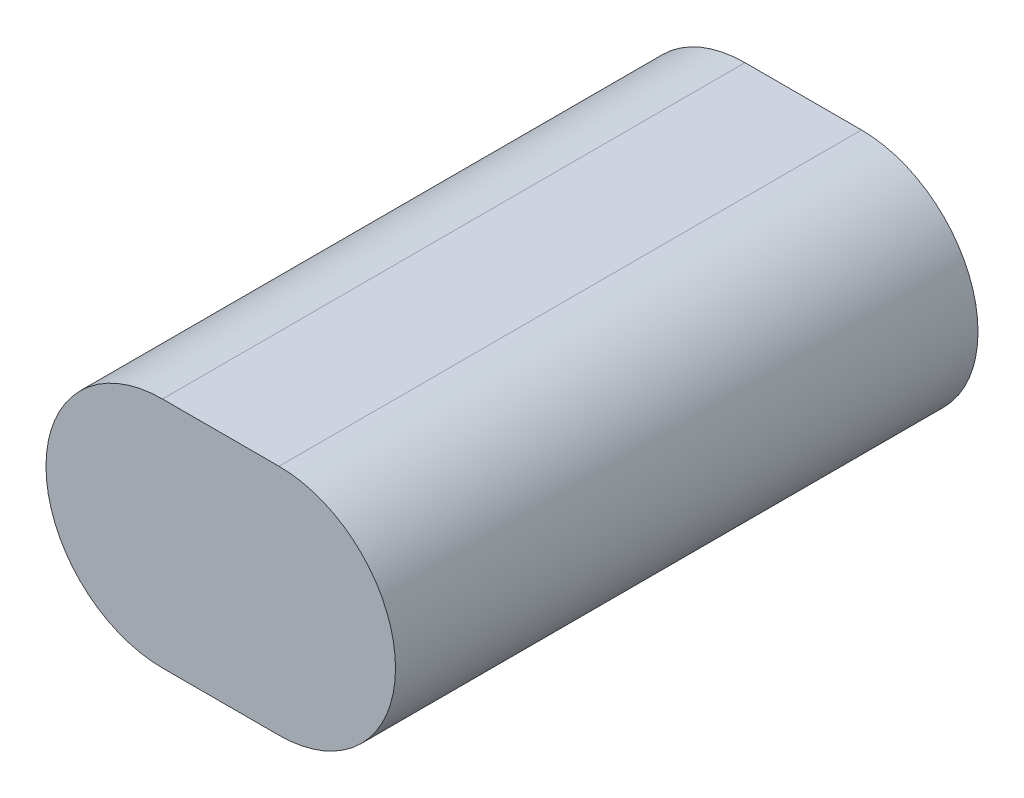
SolidWorks part; units mm, degrees
ref_plane "Front Plane" through (0, 0, 0) normal (0, 0, 1) x (1, 0, 0)
ref_plane "Top Plane" through (0, 0, 0) normal (0, 1, 0) x (1, 0, 0)
ref_plane "Right Plane" through (0, 0, 0) normal (1, 0, 0) x (0, 0, -1)
other "Configuration Table"
sketch "Sketch1" plane through (0, 0, 0) normal (0, 0, 1) x (1, 0, 0)
  line L0 (0, 0) -> (20, 0) construction
  line L1 (0, 20) -> (20, 20)
  line L2 (0, -20) -> (20, -20)
  arc A0 (0, 20) -> (0, -20) centre (0, 0) ccw
  arc A1 (20, -20) -> (20, 20) centre (20, 0) ccw
  point P3 (10, 0)
  dimension "D1" = 40
  dimension "D2" = 60
extrude "Boss-Extrude1" add sketch "Sketch1" along normal blind 100
